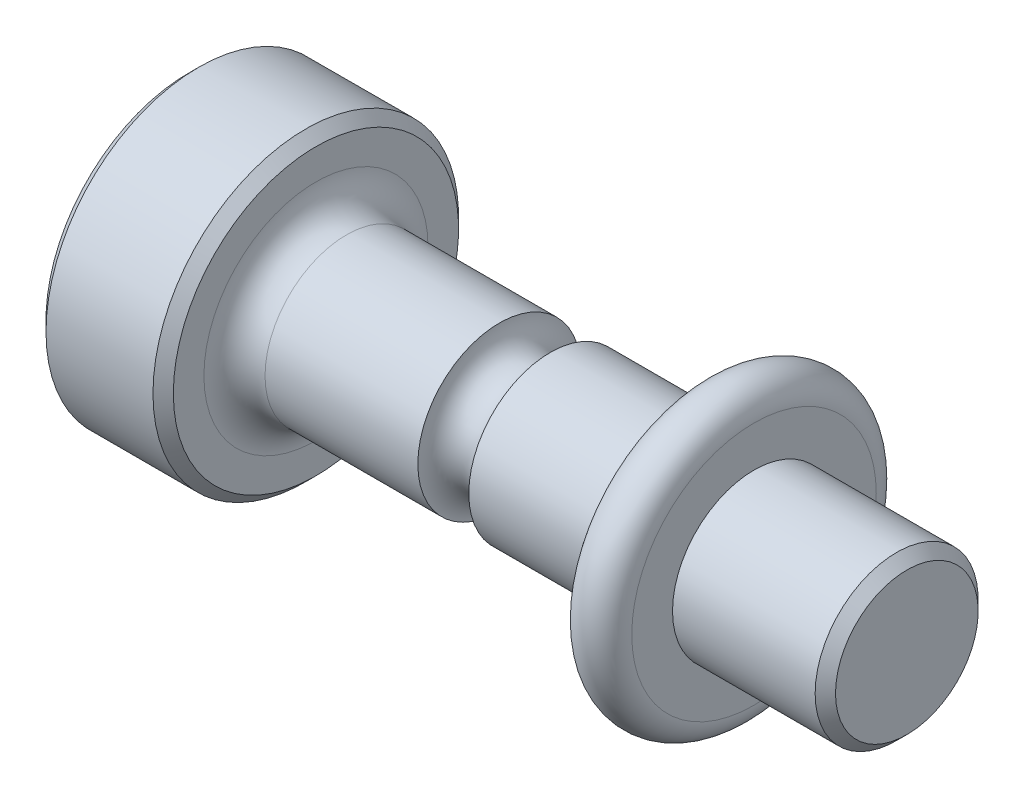
SolidWorks part; units mm, degrees
ref_plane "Front Plane" through (0, 0, 0) normal (0, 0, 1) x (1, 0, 0)
ref_plane "Top Plane" through (0, 0, 0) normal (0, 1, 0) x (1, 0, 0)
ref_plane "Right Plane" through (0, 0, 0) normal (1, 0, 0) x (0, 0, -1)
sketch "Sketch1" plane through (0, 0, 0) normal (0, 0, 1) x (1, 0, 0)
  line L0 (-31.3208, 0) -> (152.6816, 0) construction
  line L1 (0, 0) -> (141, 0)
  line L2 (141, 0) -> (141, 16)
  line L3 (141, 16) -> (111, 16)
  line L7 (101, 16) -> (71, 16)
  line L8 (61, 16) -> (31, 16)
  line L9 (25, 22) -> (25, 30)
  line L10 (25, 30) -> (0, 30)
  line L11 (0, 30) -> (0, 0)
  line L12 (101, 16) -> (101, 24)
  line L14 (111, 24) -> (111, 16)
  arc A0 (71, 16) -> (61, 16) centre (66, 16) cw
  arc A1 (31, 16) -> (25, 22) centre (31, 22) cw
  arc A3 (101, 24) -> (111, 24) centre (106, 24) cw
  point P19 (152.6816, 0)
  dimension "D3" = 6
  dimension "D6" = 5
  dimension "D8" = 5
  dimension "D1" = 30
  dimension "D2" = 8
  dimension "D4" = 25
  dimension "D5" = 30
  dimension "D7" = 30
  dimension "D9" = 30
  dimension "D10" = 141
  dimension "D11" = 8
  dimension "D12" = 106
  dimension "D13" = 16
revolve "Revolve1" add sketch "Sketch1" angle 360 about L0
chamfer "Chamfer1" distance 2 angle 45 3 edges at (141, 0, 16) (0, 0, 30) (25, 0, 30)
